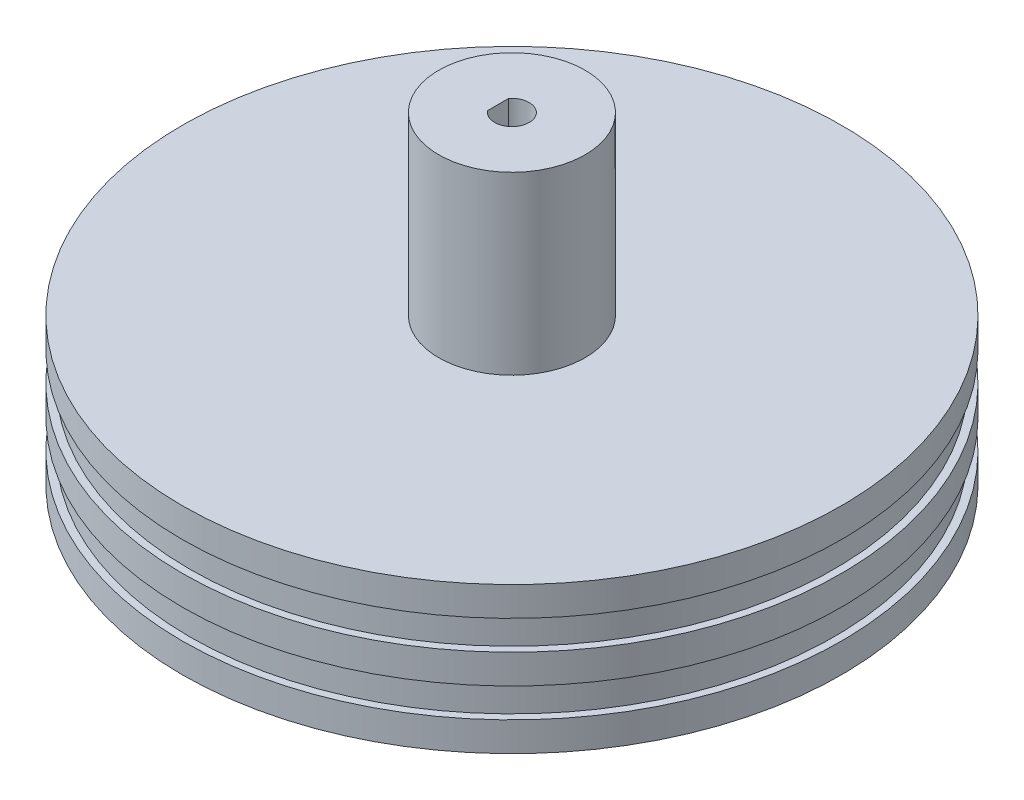
SolidWorks part; units mm, degrees
ref_plane "Front Plane" through (0, 0, 0) normal (0, 0, 1) x (1, 0, 0)
ref_plane "Top Plane" through (0, 0, 0) normal (0, 1, 0) x (1, 0, 0)
ref_plane "Right Plane" through (0, 0, 0) normal (1, 0, 0) x (0, 0, -1)
sketch "Sketch1" plane through (0, 0, 0) normal (0, 1, 0) x (1, 0, 0)
  circle A0 centre (0, 0) radius 28.575
extrude "Boss-Extrude1" add sketch "Sketch1" along normal blind 2.54 contours A0
sketch "Sketch2" plane through (0, 2.54, 0) normal (0, 1, 0) x (1, 0, 0)
  circle A0 centre (0, 0) radius 27.94
extrude "Boss-Extrude2" add sketch "Sketch2" along normal blind 2.54
sketch "Sketch3" plane through (0, 5.08, 0) normal (0, 1, 0) x (1, 0, 0)
  circle A0 centre (0, 0) radius 28.575
extrude "Boss-Extrude3" add sketch "Sketch3" along normal blind 2.54
sketch "Sketch4" plane through (0, 7.62, 0) normal (0, 1, 0) x (1, 0, 0)
  circle A0 centre (0, 0) radius 27.94
  point P3 (0, 0)
extrude "Boss-Extrude4" add sketch "Sketch4" along normal blind 2.54
sketch "Sketch5" plane through (0, 10.16, 0) normal (0, 1, 0) x (1, 0, 0)
  circle A0 centre (0, 0) radius 28.575
extrude "Boss-Extrude5" add sketch "Sketch5" along normal blind 2.54
sketch "Sketch6" plane through (0, 12.7, 0) normal (0, 1, 0) x (1, 0, 0)
  circle A0 centre (0, 0) radius 6.35
extrude "Boss-Extrude6" add sketch "Sketch6" along normal blind 15.24
sketch "Sketch7" plane through (0, 27.94, 0) normal (0, 1, 0) x (1, 0, 0)
  line L0 (-1.2, 0.9) -> (-1.2, -0.9)
  arc A0 (-1.2, -0.9) -> (-1.2, 0.9) centre (0, 0) ccw
  point P5 (0, 0)
  point P6 (0, 0)
  dimension "D1" = 1.8
extrude "Cut-Extrude1" cut sketch "Sketch7" against normal blind 12.7
